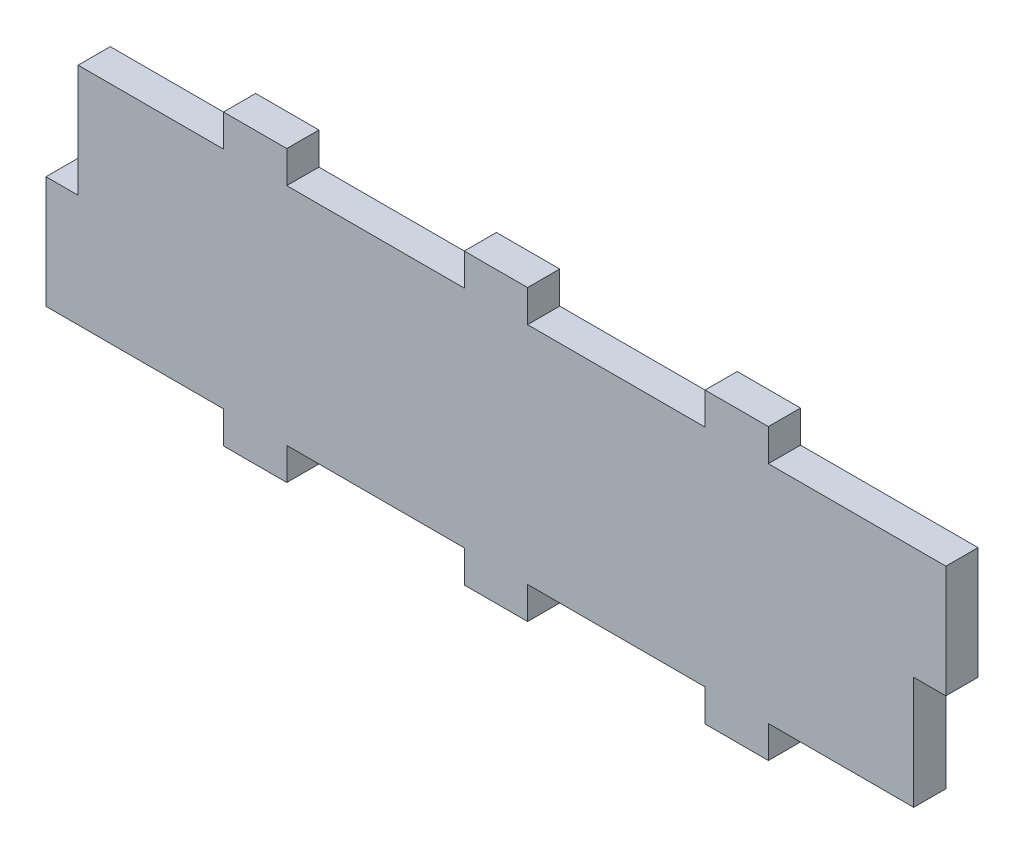
SolidWorks part; units mm, degrees
ref_plane "Front Plane" through (0, 0, 0) normal (0, 0, 1) x (1, 0, 0)
ref_plane "Top Plane" through (0, 0, 0) normal (0, 1, 0) x (1, 0, 0)
ref_plane "Right Plane" through (0, 0, 0) normal (1, 0, 0) x (0, 0, -1)
sketch "Sketch2" plane through (0, 0, 0) normal (0, 0, 1) x (1, 0, 0)
  line L0 (-42.3875, 22.5) -> (-42.3875, 17.5)
  line L1 (-65, -17.5) -> (65, -17.5)
  line L2 (-65, -17.5) -> (-65, 17.5)
  line L3 (-65, 17.5) -> (65, 17.5)
  line L4 (65, -17.5) -> (65, 17.5)
  line L5 (-65, -17.5) -> (65, 17.5) construction
  line L6 (-65, 17.5) -> (65, -17.5) construction
  line L7 (-65, -17.5) -> (-70, -17.5)
  line L8 (-65, -17.5) -> (-65, -0.025)
  line L9 (-65, -0.025) -> (-70, -0.025)
  line L10 (-70, -17.5) -> (-70, -0.025)
  line L11 (-42.3875, -17.5) -> (-32.5375, -17.5)
  line L12 (-42.3875, -17.5) -> (-42.3875, -22.5)
  line L13 (-42.3875, -22.5) -> (-32.5375, -22.5)
  line L14 (-32.5375, -17.5) -> (-32.5375, -22.5)
  line L15 (-4.925, -17.5) -> (4.925, -17.5)
  line L16 (-4.925, -17.5) -> (-4.925, -22.5)
  line L17 (-4.925, -22.5) -> (4.925, -22.5)
  line L18 (4.925, -17.5) -> (4.925, -22.5)
  line L19 (32.5375, -17.5) -> (42.3875, -17.5)
  line L20 (32.5375, -17.5) -> (32.5375, -22.5)
  line L21 (32.5375, -22.5) -> (42.3875, -22.5)
  line L22 (42.3875, -17.5) -> (42.3875, -22.5)
  line L23 (65, 17.5) -> (70, 17.5)
  line L24 (65, 17.5) -> (65, 0.025)
  line L25 (65, 0.025) -> (70, 0.025)
  line L26 (70, 17.5) -> (70, 0.025)
  line L27 (-42.3875, 22.5) -> (-32.5375, 22.5)
  line L28 (-32.5375, 22.5) -> (-32.5375, 17.5)
  line L29 (-42.3875, 17.5) -> (-32.5375, 17.5)
  line L30 (-4.925, 22.5) -> (-4.925, 17.5)
  line L31 (-4.925, 22.5) -> (4.925, 22.5)
  line L32 (4.925, 22.5) -> (4.925, 17.5)
  line L33 (-4.925, 17.5) -> (4.925, 17.5)
  line L34 (32.5375, 22.5) -> (32.5375, 17.5)
  line L35 (32.5375, 22.5) -> (42.3875, 22.5)
  line L36 (42.3875, 22.5) -> (42.3875, 17.5)
  line L37 (32.5375, 17.5) -> (42.3875, 17.5)
  line L38 (32.5375, -20) -> (4.925, -20) construction
  line L39 (-4.925, -20) -> (-32.5375, -20) construction
  line L42 (42.3875, -20) -> (70, -20) construction
  line L43 (70, -20) -> (70, 0.025) construction
  line L44 (-42.3875, -20) -> (-70, -20) construction
  line L45 (-70, -20) -> (-70, -17.5) construction
  point P0 (0, 0)
  dimension "D1" = 35
  dimension "D2" = 130
  dimension "D3" = 17.475
  dimension "D4" = 5
  dimension "D5" = 5
  dimension "D6" = 5
  dimension "D7" = 5
  dimension "D8" = 9.85
  dimension "D9" = 9.85
  dimension "D10" = 9.85
  dimension "D13" = 5
  dimension "D14" = 17.475
  dimension "D16" = 2
extrude "Boss-Extrude1" add sketch "Sketch2" along normal blind 5 contours L1 L4 L3 L2 | L10 L7 L2 L9 | L28 L27 L0 L3 | L32 L31 L30 L3 | L36 L35 L34 L3 | L26 L23 L4 L25 | L22 L1 L20 L21 | L18 L1 L16 L17 | L14 L1 L12 L13
